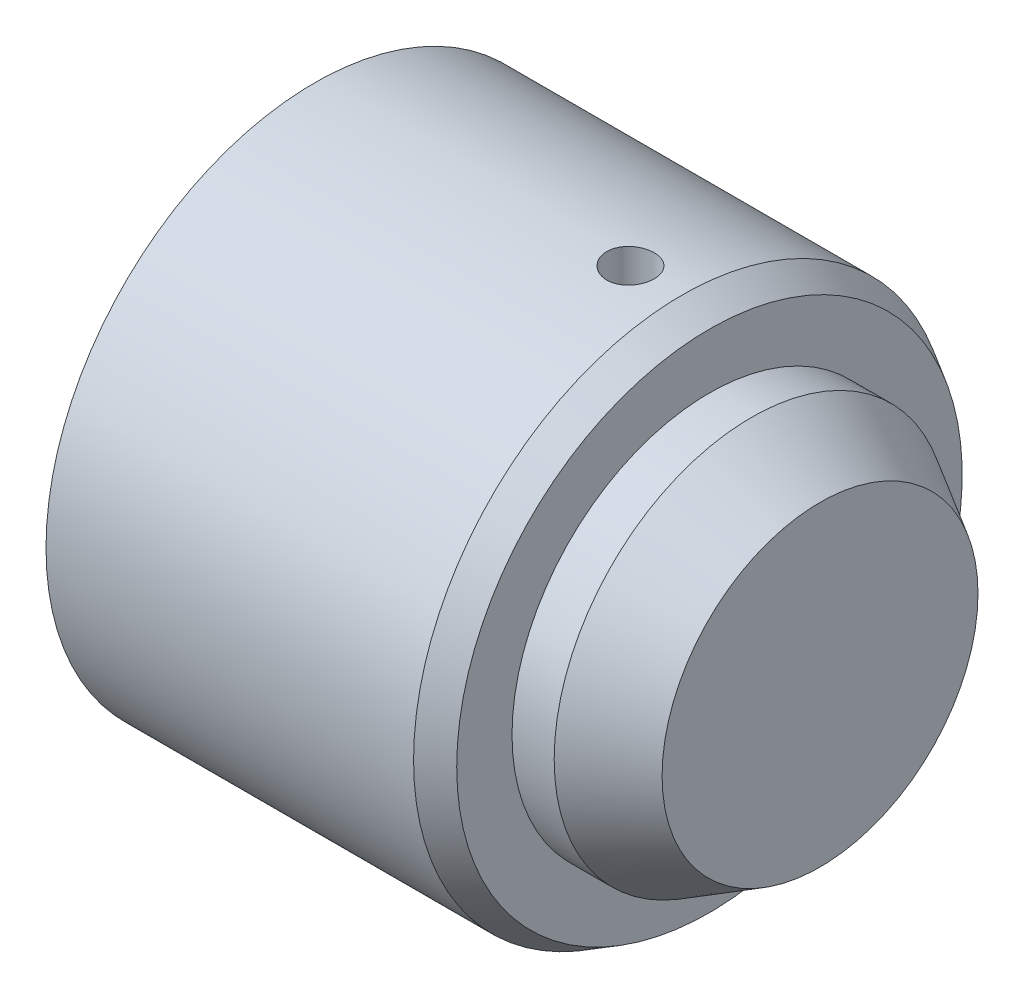
SolidWorks part; units mm, degrees
ref_plane "前视基准面" through (0, 0, 0) normal (0, 0, 1) x (1, 0, 0)
ref_plane "上视基准面" through (0, 0, 0) normal (0, 1, 0) x (1, 0, 0)
ref_plane "右视基准面" through (0, 0, 0) normal (1, 0, 0) x (0, 0, -1)
sketch "草图1"
  line L0 (0, 0) -> (0, 12.5)
  line L1 (0, 12.5) -> (-7, 12.5)
  line L2 (-7, 12.5) -> (-7, 17)
  line L3 (-7, 17) -> (-32, 17)
  line L4 (-32, 17) -> (-32, 14)
  line L5 (-32, 14) -> (-10, 14)
  line L6 (-10, 14) -> (-10, 0)
  line L7 (-10, 0) -> (0, 0)
other "对齐组1" parameters "D1"=0, "D2"=12.5, "D3"=17, "D4"=16.3017, "D5"=7, "D6"=10, "D7"=32, "D8"=22
other "对齐组2"
other "对齐组3"
revolve "旋转1" add sketch "草图1" angle 360 about L7
chamfer "倒角1" distance 2.5 angle 60 1 edges at (0, 0, 12.5)
chamfer "倒角2" distance 1 angle 60 1 edges at (-7, 0, 17)
sketch "草图2" plane through (-10, 0, 0) normal (-1, 0, 0) x (0, 0, 1)
  point P0 (0, 0)
  point P1 (0, 0)
hole_wizard "M6 螺纹孔1" positions "3D草图1" profile "草图3" tap size "M6" standard "GB"
sketch3d "3D草图1"
  point P0 (-10, 0, 0)
sketch "草图3" plane through (-10, 0, 0) normal (0, 1, 0) x (0, 0, 1)
  line L0 (0, 0) -> (0, 9.5022)
  line L1 (0, 9.5022) -> (2.5, 8)
  line L2 (2.5, 8) -> (2.5, 1.5)
  line L3 (2.5, 1.5) -> (4, 0)
  line L5 (4, 0) -> (0, 0)
  line L6 (-2.5, 1.5) -> (-4, 0) construction
  line L10 (0, 9.5022) -> (-2.5, 8) construction
  line L11 (0, -6.35) -> (0, 107.95) construction
  dimension "螺纹孔钻头直径" = 5
  dimension "螺纹孔钻头深度" = 8
  dimension "近端锥形沉头孔直径" = 8
  dimension "近端锥形沉头孔角度" = 90
  dimension "导头角度" = 118
cosmetic thread "孔螺蚊线1"
sketch "草图4" plane through (0, 0, 0) normal (0, 1, 0) x (1, 0, 0)
  line L0 (-32, 17) -> (-32, -17) construction
  circle A0 centre (-12, 0) radius 1.5
  point P2 (0, 0)
  point P4 (0, 0)
  dimension "D1" = 3
  dimension "D2" = 20
extrude "切除-拉伸1" cut sketch "草图4" against normal mid plane 40
